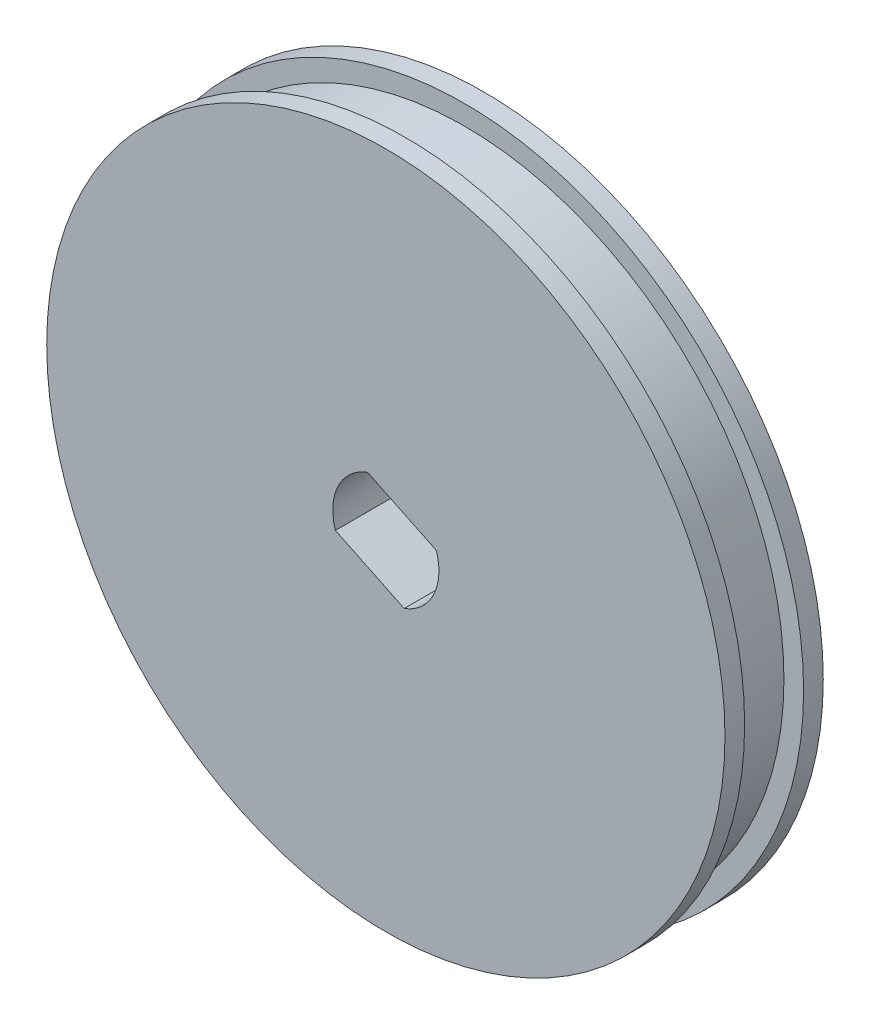
SolidWorks part; units mm, degrees
ref_plane "前视基准面" through (0, 0, 0) normal (0, 0, 1) x (1, 0, 0)
ref_plane "上视基准面" through (0, 0, 0) normal (0, 1, 0) x (1, 0, 0)
ref_plane "右视基准面" through (0, 0, 0) normal (1, 0, 0) x (0, 0, -1)
sketch "草图1" plane through (0, 0, 0) normal (0, 0, 1) x (1, 0, 0)
  circle A0 centre (22.4165, -13.7077) radius 16.25
  dimension "D1" = 32.5
extrude "凸台-拉伸1" add sketch "草图1" along normal mid plane 3
sketch "草图2" plane through (0, 0, 1.5) normal (0, 0, 1) x (1, 0, 0)
  circle A2 centre (22.4165, -13.7077) radius 17.25
  circle A3 centre (22.4165, -13.7077) radius 17.25
  dimension "D1" = 1
extrude "凸台-拉伸2" add sketch "草图2" along normal blind 1
mirror "镜向1" about plane through (0, 0, 0) normal (0, 0, 1) of "凸台-拉伸2"
sketch "草图3" plane through (0, 0, 2.5) normal (0, 0, 1) x (1, 0, 0)
  line L0 (24.9818, -12.8655) -> (21.4839, -11.1739) construction
  line L1 (19.8512, -14.5498) -> (23.3492, -16.2415) construction
  line L2 (24.9818, -12.8655) -> (21.4839, -11.1739)
  line L3 (19.8512, -14.5498) -> (23.3492, -16.2415)
  arc A0 (21.4839, -11.1739) -> (19.8512, -14.5498) centre (22.4165, -13.7077) ccw construction
  arc A1 (23.3492, -16.2415) -> (24.9818, -12.8655) centre (22.4165, -13.7077) ccw construction
  arc A3 (21.4839, -11.1739) -> (19.8512, -14.5498) centre (22.4165, -13.7077) ccw
  arc A4 (23.3492, -16.2415) -> (24.9818, -12.8655) centre (22.4165, -13.7077) ccw
extrude "切除-拉伸1" cut sketch "草图3" against normal through all
